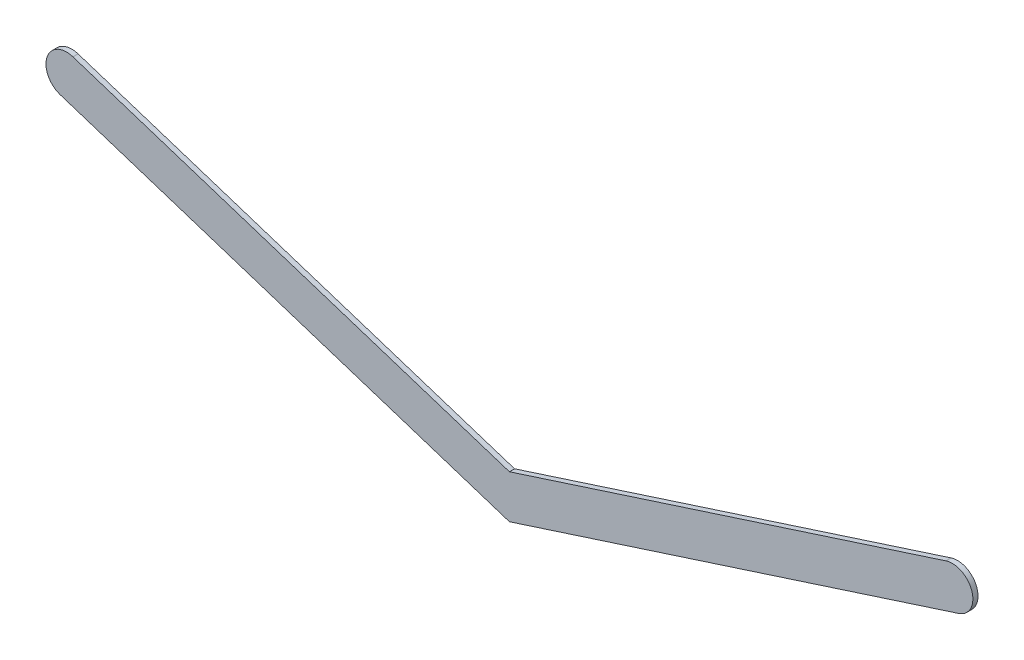
SolidWorks part; units mm, degrees
material "Plain Carbon Steel"
ref_plane "Front Plane" through (0, 0, 0) normal (0, 0, 1) x (1, 0, 0)
ref_plane "Top Plane" through (0, 0, 0) normal (0, 1, 0) x (1, 0, 0)
ref_plane "Right Plane" through (0, 0, 0) normal (1, 0, 0) x (0, 0, -1)
sketch "Sketch1" plane through (0, 0, 0) normal (0, 0, 1) x (1, 0, 0)
  line L0 (546.1, 0) -> (-546.1, 0) construction
  line L1 (55, 0) -> (-55, 0) construction
  line L4 (-553.9117, -24.1689) -> (0, -203.2)
  line L5 (0, -203.2) -> (553.9117, -24.1689)
  line L7 (0, -55) -> (0, 55) construction
  line L8 (-538.2883, 24.1689) -> (0, -149.8125)
  line L9 (0, -149.8125) -> (538.2883, 24.1689)
  arc A0 (553.9117, -24.1689) -> (538.2883, 24.1689) centre (546.1, 0) ccw
  arc A1 (-538.2883, 24.1689) -> (-553.9117, -24.1689) centre (-546.1, 0) ccw
  point P5 (0, 0)
  point P10 (0, -142.9665)
  point P12 (0, 0)
  point P13 (512.0163, 0)
  point P16 (0, 0)
  dimension "D1" = 50.8
  dimension "D2" = 1143
  dimension "D3" = 203.2
extrude "Boss-Extrude1" add sketch "Sketch1" along normal mid plane 6.35
